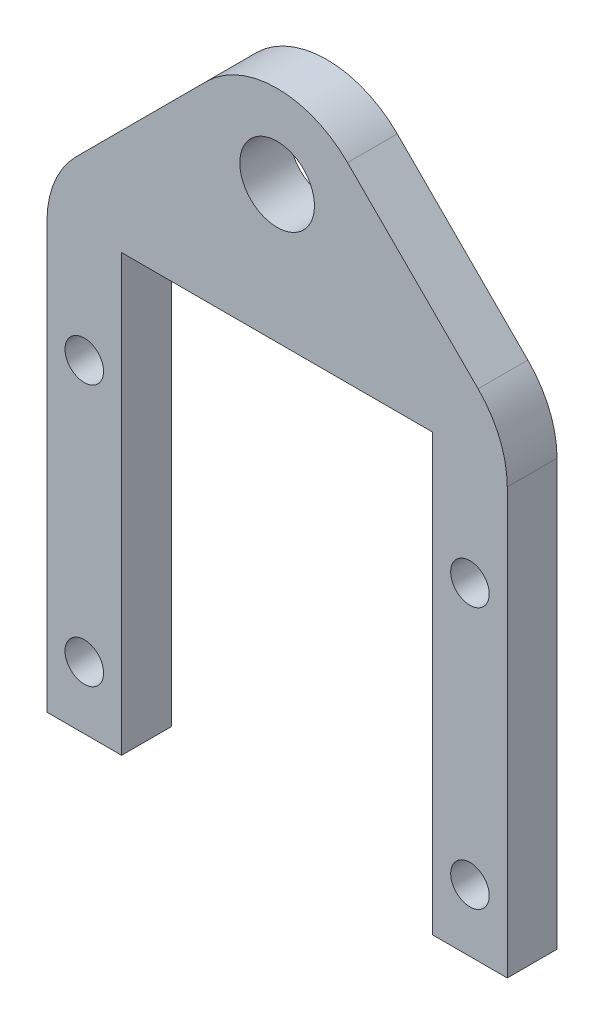
SolidWorks part; units mm, degrees
ref_plane "前视基准面" through (0, 0, 0) normal (0, 0, 1) x (1, 0, 0)
ref_plane "上视基准面" through (0, 0, 0) normal (0, 1, 0) x (1, 0, 0)
ref_plane "右视基准面" through (0, 0, 0) normal (1, 0, 0) x (0, 0, -1)
sketch "草图1" plane through (0, 0, 0) normal (0, 0, 1) x (1, 0, 0)
  line L0 (-12.5, 0) -> (-18.5, 0)
  line L2 (-12.5, 0) -> (-12.5, 35)
  line L3 (-12.5, 35) -> (12.5, 35)
  line L4 (12.5, 0) -> (12.5, 35)
  line L5 (-18.5, 0) -> (-18.5, 37.5)
  line L6 (-18.5, 37.5) -> (0, 56)
  line L7 (0, 56) -> (18.5, 37.5)
  line L8 (18.5, 37.5) -> (18.5, 0)
  line L9 (18.5, 0) -> (12.5, 0)
  line L10 (0, 56) -> (0, 0) construction
  circle A0 centre (0, 46) radius 3
  circle A2 centre (-15.5, 5) radius 1.55
  circle A3 centre (-15.5, 26) radius 1.55
  circle A4 centre (15.5, 5) radius 1.55
  circle A5 centre (15.5, 26) radius 1.55
  point P21 (0, 0)
  point P22 (0, 0)
  point P23 (0, 0)
  point P24 (0, 0)
  point P25 (0, 0)
  point P26 (0, 0)
  point P27 (0, 0)
  point P28 (0, 0)
extrude "凸台-拉伸1" add sketch "草图1" along normal blind 4
fillet "圆角1" radius 8 3 edges at (-18.5, 37.5, 2) (18.5, 37.5, 2) (0, 56, 2)
